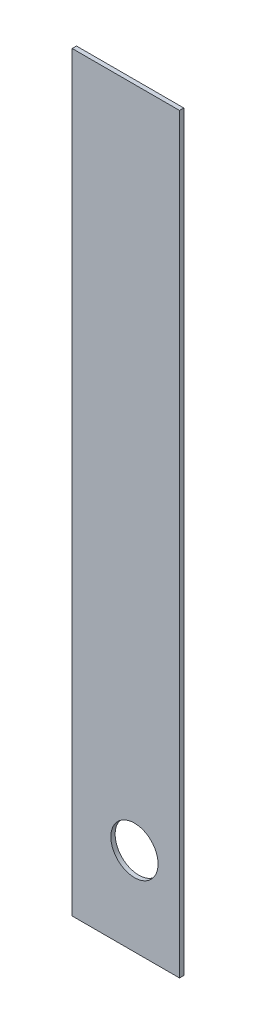
SolidWorks part; units mm, degrees
ref_plane "Front Plane" through (0, 0, 0) normal (0, 0, 1) x (1, 0, 0)
ref_plane "Top Plane" through (0, 0, 0) normal (0, 1, 0) x (1, 0, 0)
ref_plane "Right Plane" through (0, 0, 0) normal (1, 0, 0) x (0, 0, -1)
sketch "Sketch1" plane through (0, 0, 0) normal (0, 1, 0) x (1, 0, 0)
  line L1 (25, -1) -> (-25, -1)
  line L2 (25, -1) -> (25, 1)
  line L3 (25, 1) -> (-25, 1)
  line L4 (-25, -1) -> (-25, 1)
  line L5 (25, -1) -> (-25, 1) construction
  line L6 (25, 1) -> (-25, -1) construction
  point P0 (0, 0)
extrude "Boss-Extrude1" add sketch "Sketch1" along normal blind 200 and the other way up to surface (150 mm away)
sketch "Sketch2" plane through (0, 0, -1) normal (0, 0, -1) x (-1, 0, 0)
  circle A0 centre (-4, -109) radius 11
extrude "Cut-Extrude1" cut sketch "Sketch2" against normal through all
